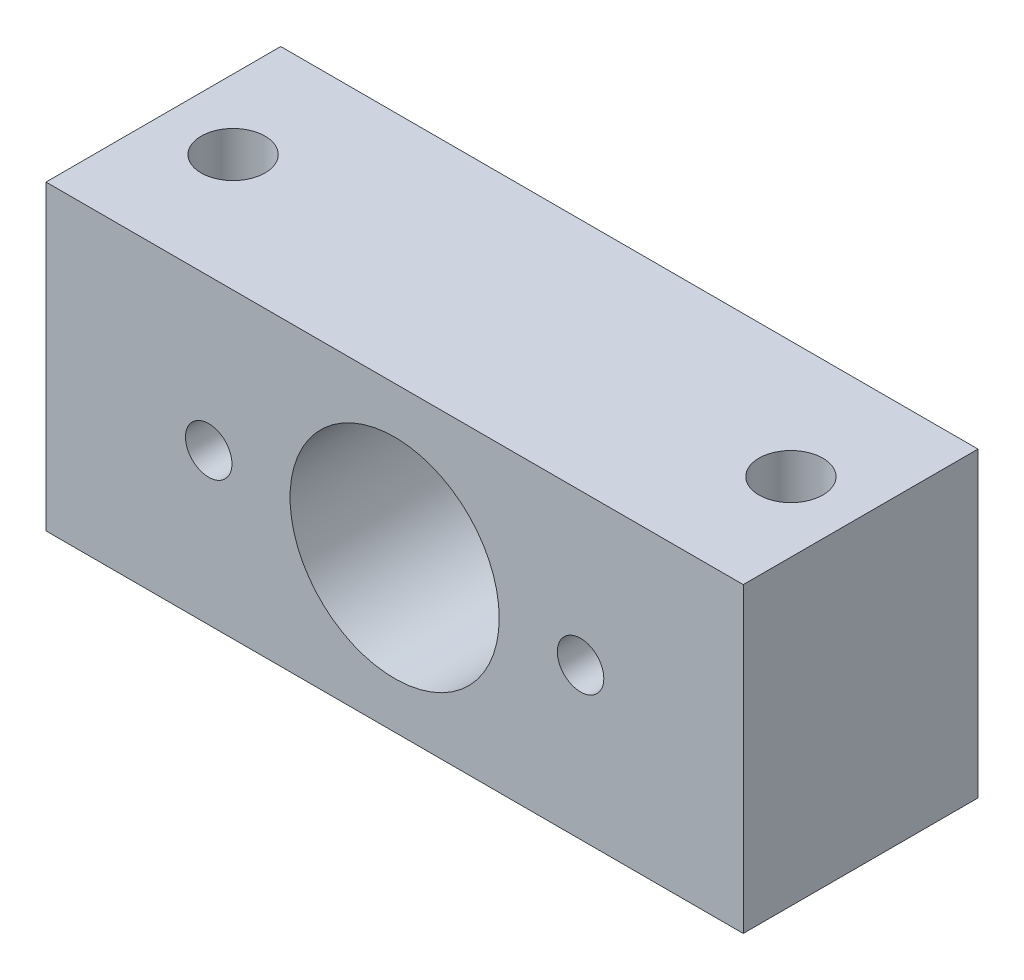
SolidWorks part; units mm, degrees
material "ABS PC"
ref_plane "Front Plane" through (0, 0, 0) normal (0, 0, 1) x (1, 0, 0)
ref_plane "Top Plane" through (0, 0, 0) normal (0, 1, 0) x (1, 0, 0)
ref_plane "Right Plane" through (0, 0, 0) normal (1, 0, 0) x (0, 0, -1)
sketch "Sketch1" plane through (0, 0, 0) normal (0, 0, 1) x (1, 0, 0)
  line L0 (0, 0) -> (60, 0)
  line L1 (0, 0) -> (0, 26)
  line L2 (60, 0) -> (60, 26)
  line L3 (0, 26) -> (60, 26)
  dimension "D1" = 60
  dimension "D2" = 26
extrude "Boss-Extrude1" add sketch "Sketch1" along normal blind 20.2
sketch "Sketch2" plane through (0, 0, 20.2) normal (0, 0, 1) x (1, 0, 0)
  line L0 (0, 26) -> (0, 0) construction
  line L1 (0, 0) -> (60, 0) construction
  circle A0 centre (30, 13) radius 9
  circle A1 centre (14, 13) radius 2
  circle A2 centre (46, 13) radius 2
  point P2 (0, 13)
  dimension "D1" = 18
  dimension "D2" = 30
  dimension "D3" = 13
  dimension "D4" = 4
  dimension "D5" = 16
  dimension "D6" = 16
extrude "Cut-Extrude1" cut sketch "Sketch2" against normal through all
sketch "Sketch3" plane through (0, 0, 0) normal (0, 0, -1) x (-1, 0, 0)
  circle A0 centre (-30, 13) radius 11.5
  dimension "D1" = 23
extrude "Cut-Extrude2" cut sketch "Sketch3" against normal blind 4
hole_wizard "Ø5.5 (5.5) Diameter Hole1" positions "Sketch5" profile "Sketch4" hole size "Ø5.5" standard "Ansi Metric"
sketch "Sketch5" plane through (0, 26, 0) normal (0, 1, 0) x (-1, 0, 0)
  line L0 (-60, 20.2) -> (0, 20.2) construction
  line L1 (0, 20.2) -> (0, 0) construction
  line L2 (-60, 20.2) -> (-60, 0) construction
  point P0 (-6, 10.1)
  point P1 (-54, 10.1)
  dimension "D1" = 10.1
  dimension "D2" = 6
  dimension "D3" = 6
sketch "Sketch4" plane through (6, 26, 10.1) normal (1, 0, 0) x (0, 0, 1)
  line L0 (0, 0) -> (0, 31.6524)
  line L1 (0, 31.6524) -> (2.75, 30)
  line L2 (2.75, 30) -> (2.75, 0)
  line L5 (2.75, 0) -> (0, 0)
  line L10 (0, 31.6524) -> (-2.75, 30) construction
  line L11 (0, -6.35) -> (0, 107.95) construction
  dimension "Hole Dia." = 5.5
  dimension "Hole Depth" = 30
  dimension "Drill Angle" = 118
